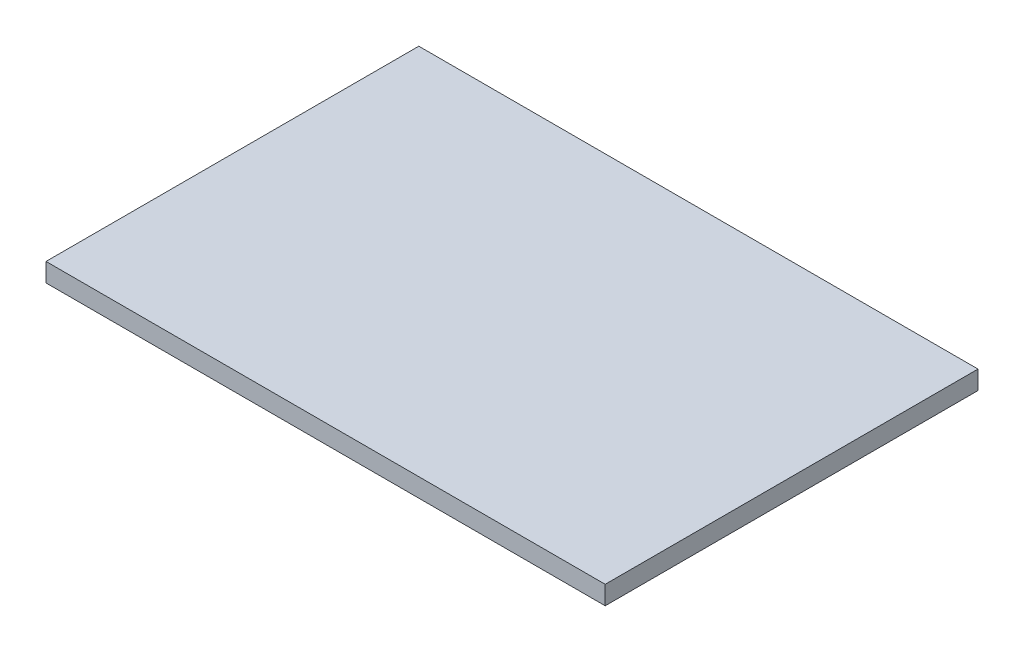
SolidWorks part; units mm, degrees
ref_plane "Alzado" through (0, 0, 0) normal (0, 0, 1) x (1, 0, 0)
ref_plane "Planta" through (0, 0, 0) normal (0, 1, 0) x (1, 0, 0)
ref_plane "Vista lateral" through (0, 0, 0) normal (1, 0, 0) x (0, 0, -1)
sketch "Croquis1" plane through (0, 0, 0) normal (0, 1, 0) x (1, 0, 0)
  line L1 (-150, -100) -> (150, -100)
  line L2 (-150, -100) -> (-150, 100)
  line L3 (-150, 100) -> (150, 100)
  line L4 (150, -100) -> (150, 100)
  line L5 (-150, -100) -> (150, 100) construction
  line L6 (-150, 100) -> (150, -100) construction
  point P0 (0, 0)
  dimension "D1" = 300
  dimension "D2" = 200
extrude "Saliente-Extruir1" add sketch "Croquis1" along normal blind 10
